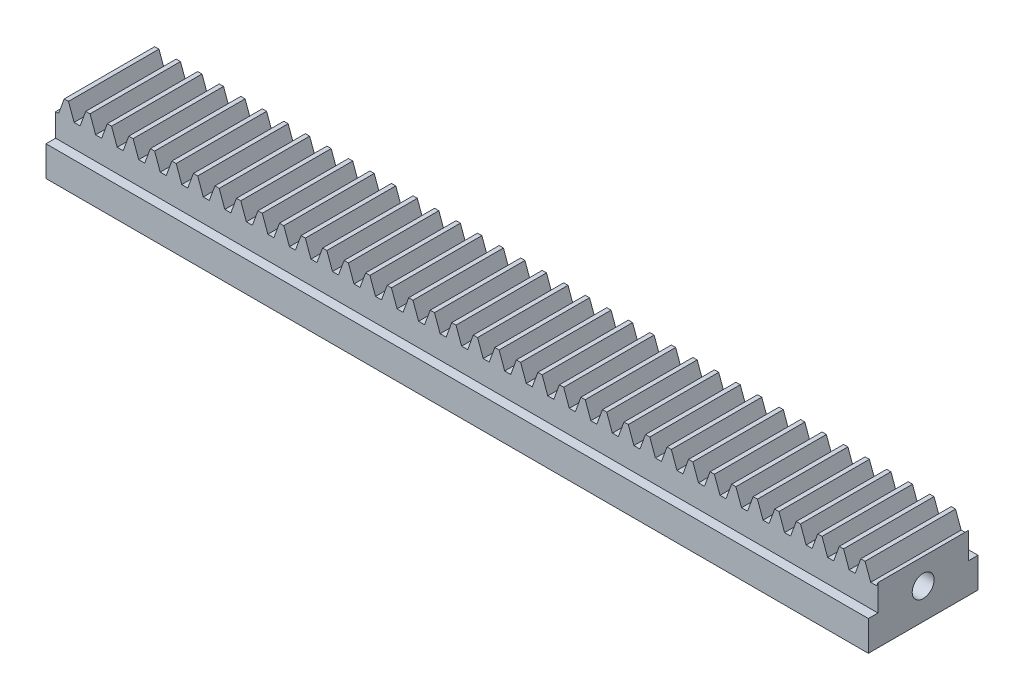
SolidWorks part; units mm, degrees
extrude "Blank" add sketch "BlankSke" against normal blind 20
sketch "BlankSke" plane through (0, 0, 0) normal (0, 0, 1) x (1, 0, 0)
  line L1 (0, 0) -> (150, 0)
  line L2 (0, 0) -> (0, 12.5)
  line L3 (0, 12.5) -> (150, 12.5)
  line L4 (150, 0) -> (150, 12.5)
  dimension "Length" = 150
  dimension "Blank_height" = 12.5
ref_plane "Plane1" through (0, 0, 0) normal (0, 0, 1) x (1, 0, 0)
ref_plane "Plane2" through (0, 0, 0) normal (0, 1, 0) x (1, 0, 0)
ref_plane "Plane3" through (0, 0, 0) normal (1, 0, 0) x (0, 0, -1)
other "Configuration Table"
sketch "HoldingSke" plane through (0, 0, 0) normal (0, 1, 0) x (1, 0, 0)
  line L0 (0, 0) -> (0.1113, 0.7922)
  line L1 (-15, 0) -> (100, 0) construction
  line L2 (0, 0) -> (-2.1039, 2.3779)
  line L3 (0, 0) -> (-11.863, 4.5341)
  line L4 (0, 0) -> (6.6156, 5.5511)
  line L5 (0, 0) -> (-23.7986, -8.8762)
  line L6 (0, 0) -> (-10.5278, -7.1032)
  line L9 (-71.009, 38.7566) -> (69.9449, 90.0596)
  line L10 (-76.2, 3.6279) -> (-64.95, 3.6279)
  line L11 (0, 0) -> (-7, 0)
  line L12 (-76.2, 101.6) -> (-76.155, 101.6)
  line L13 (24.9733, 27.94) -> (52.9518, 28.4284)
  line L14 (24.9733, 27.94) -> (24.9743, 27.94)
  line L15 (24.9733, 27.94) -> (100.4006, 29.5858)
  circle A0 centre (0, 0) radius 19.05
  circle A1 centre (0, 0) radius 5.625
  circle A2 centre (0, 0) radius 12.7
  dimension "MPH" = 11.25
  dimension "Diameter" = 38.1
  dimension "Num_teeth" = 40
  dimension "Pitch" = 0.8
  dimension "Show_teeth" = 998
  dimension "Thickness" = 12.7
  dimension "Ap" = 20
  dimension "Pitch_height" = 11.25
  dimension "Width" = 7
  dimension "Backlash" = 0.045
  dimension "Addendum_fac" = 1
  dimension "Dedendum_fac" = 1.25
  dimension "Clearance_fac" = 0.25
  dimension "Dedendum_add" = 0.001
  dimension "Length" = 150
  dimension "Module" = 1.25
sketch "TooCutSkeIll" plane through (0, 0, 0) normal (0, 0, 1) x (1, 0, 0)
  line L0 (-1.5597, 12.4671) -> (-0.6231, 9.8938)
  line L1 (-0.3285, 9.6875) -> (0.3285, 9.6875)
  line L2 (0.6231, 9.8938) -> (1.5597, 12.4671)
  line L3 (150, 12.5) -> (0, 12.5) construction
  line L4 (0, 0) -> (0, 64.897) construction
  line L5 (-13.208, 11.25) -> (12.954, 11.25) construction
  line L6 (0, 0) -> (150, 0) construction
  line L7 (1.1167, 11.25) -> (1.1167, 48.7463) construction
  line L8 (-1.1167, 11.25) -> (-1.1167, 48.7463) construction
  line L9 (1.6067, 12.5) -> (1.6067, 12.5254)
  line L10 (-1.6067, 12.5) -> (-1.6067, 12.5254)
  line L11 (-1.6067, 12.5254) -> (1.6067, 12.5254)
  arc A0 (0.3285, 9.6875) -> (0.6231, 9.8938) centre (0.3285, 10.001) ccw
  arc A1 (-0.6231, 9.8938) -> (-0.3285, 9.6875) centre (-0.3285, 10.001) ccw
  arc A2 (1.6067, 12.5) -> (1.5597, 12.4671) centre (1.6067, 12.45) ccw
  arc A3 (-1.5597, 12.4671) -> (-1.6067, 12.5) centre (-1.6067, 12.45) ccw
  dimension "Pitch_height" = 11.25
  dimension "Addendum_plus" = 1.2754
  dimension "Pressure_angle" = 20
  dimension "Gap_width" = 2.2335
  dimension "Dedendum" = 1.5625
extrude "ToothCutIll" [suppressed] cut sketch "TooCutSkeIll" against normal through all
sketch "TooCutSkeSim" plane through (0, 0, 0) normal (0, 0, 1) x (1, 0, 0)
  line L0 (0.548, 9.6875) -> (-0.548, 9.6875)
  line L1 (1.581, 12.5254) -> (0.548, 9.6875)
  line L2 (0, 17.4625) -> (0, 53.467) construction
  line L3 (1.581, 12.5254) -> (-1.581, 12.5254)
  line L6 (-1.581, 12.5254) -> (-0.548, 9.6875)
  line L9 (-1.1167, 11.25) -> (1.1167, 11.25) construction
  line L10 (0, 0) -> (150, 0) construction
  line L11 (1.1167, 11.25) -> (1.1167, 53.467) construction
  line L12 (-1.1167, 11.25) -> (-1.1167, 53.467) construction
  dimension "Pitch_height" = 11.25
  dimension "Addendum_plus" = 1.2754
  dimension "Pressure_angle" = 20
  dimension "Gap_width" = 2.2335
  dimension "Dedendum" = 1.5625
extrude "ToothCutSim" cut sketch "TooCutSkeSim" against normal through all
pattern_linear "TeethCuts" count 39 spacing 3.927 along (1, 0, 0) of "ToothCutIll", "ToothCutSim"
sketch "Croquis3" plane through (0, 0, 0) normal (0, 0, 1) x (1, 0, 0)
  line L0 (0, 9.6875) -> (0, 0) construction
  line L1 (0, 5.5) -> (150.5773, 5.5)
  line L2 (0, 5.5) -> (0, 12.8527)
  line L3 (0, 12.8527) -> (150.5773, 12.8527)
  line L4 (150.5773, 5.5) -> (150.5773, 12.8527)
  line L5 (123.408, 0) -> (123.408, 5.5) construction
  line L6 (0, 0) -> (150, 0) construction
  dimension "D1" = 5.5
extrude "Cortar-Extruir1" cut sketch "Croquis3" against normal blind 1.75
sketch "Croquis4" plane through (0, 0, -20) normal (0, 0, -1) x (-1, 0, 0)
  line L0 (-150, 0) -> (-150, 10.3093) construction
  line L1 (-150, 5.5) -> (0, 5.5)
  line L2 (-150, 5.5) -> (-150, 14.4015)
  line L3 (-150, 14.4015) -> (0, 14.4015)
  line L4 (0, 5.5) -> (0, 14.4015)
  line L5 (0, 0) -> (-150, 0) construction
  dimension "D1" = 5.5
extrude "Cortar-Extruir2" cut sketch "Croquis4" against normal blind 1.75
sketch "Croquis5" plane through (150, 0, 0) normal (1, 0, 0) x (0, 0, -1)
  line L0 (0, 0) -> (18.25, 10.3093) construction
  line L1 (18.25, 10.3093) -> (1.75, 10.3093) construction
  line L2 (1.75, 10.3093) -> (20, 0) construction
  circle A0 centre (10, 5.6489) radius 2
  dimension "D1" = 4
extrude "Cortar-Extruir3" cut sketch "Croquis5" against normal blind 10
equation "' \"Module@HoldingSke\" = 6.35"
equation "' \"Num_teeth@HoldingSke\" = 12"
equation "' \"Ap@HoldingSke\" =  20"
equation "' \"Ap@HoldingSke\" = 20"
equation "' \"Width@HoldingSke\" = 0.25 * 25.4"
equation "' \"Show_teeth@HoldingSke\" = 500"
equation "' \"Backlash@HoldingSke\" = 0.009 * 25.4"
equation "' \"Addendum_fac@HoldingSke\" = 1.0"
equation "' \"Dedendum_fac@HoldingSke\" = 1.25"
equation "' \"Dedendum_add@HoldingSke\" = 0.00005 * 25.4"
equation "' \"Clearance_fac@HoldingSke\" = 0.25"
equation "' \"Pitch_height@HoldingSke\" = 1 * 25.4"
equation "' \"Length@HoldingSke\" = 4.71 * 25.4"
equation "\"Pitch@HoldingSke\" = 1 / \"Module@HoldingSke\""
equation "\"MPH@HoldingSke\" = \"Dedendum_fac@HoldingSke\" / \"Pitch@HoldingSke\" + 2 * \"Dedendum_add@HoldingSke\" + 0.002 * 25.4"
equation "\"MPH@HoldingSke\" = ((sgn( \"MPH@HoldingSke\" - \"Pitch_height@HoldingSke\")+1)*( \"MPH@HoldingSke\" - \"Pitch_height@HoldingSke\"))/2 + \"Pitch_height@HoldingSke\""
equation "\"Blank_height@BlankSke\" = \"Pitch_height@HoldingSke\" + \"Addendum_fac@HoldingSke\"  / \"Pitch@HoldingSke\" "
equation "\"Length@BlankSke\" =  \"Length@HoldingSke\""
equation "\"Pressure_angle@TooCutSkeIll\" = \"Ap@HoldingSke\""
equation "\"Addendum_plus@TooCutSkeIll\" =  \"Addendum_fac@HoldingSke\"  / \"Pitch@HoldingSke\" + 0.001 *25.4"
equation "\"Dedendum@TooCutSkeIll\" = \"Dedendum_fac@HoldingSke\"  / \"Pitch@HoldingSke\""
equation "\"Pitch_height@TooCutSkeIll\" =  \"MPH@HoldingSke\""
equation "\"Gap_width@TooCutSkeIll\" = 3.14159265 / 2 / \"Pitch@HoldingSke\" + 6 * \"Backlash@HoldingSke\""
equation "\"Pressure_angle@TooCutSkeSim\" = \"Ap@HoldingSke\""
equation "\"Addendum_plus@TooCutSkeSim\" =  \"Addendum_fac@HoldingSke\"  / \"Pitch@HoldingSke\" + 0.001 * 25.4"
equation "\"Dedendum@TooCutSkeSim\" = \"Dedendum_fac@HoldingSke\"  / \"Pitch@HoldingSke\""
equation "\"Pitch_height@TooCutSkeSim\" =  \"MPH@HoldingSke\""
equation "\"Gap_width@TooCutSkeSim\" = 3.14159265 / 2 / \"Pitch@HoldingSke\" + 6 * \"Backlash@HoldingSke\""
equation "\"Root_fillet@TooCutSkeIll\" = \"Clearance_fac@HoldingSke\" / \"Pitch@HoldingSke\" + \"Dedendum_add@HoldingSke\""
equation "\"Break_rad@TooCutSkeIll\" = 0.02 / \"Pitch@HoldingSke\" * 2"
equation "\"Linear_pitch@TeethCuts\" = 3.14159265 / \"Pitch@HoldingSke\""
equation "\"Num_teeth@HoldingSke\" = int( ( \"Length@HoldingSke\" + 0 ) / (3.14159265 / \"Pitch@HoldingSke\")) + 0.9999  + 1"
equation " \"Num_teeth@TeethCuts\" = int( \"Show_teeth@HoldingSke\" ) + 1"
equation " \"Num_teeth@TeethCuts\" = ((sgn( \"Num_teeth@TeethCuts\" - \"Num_teeth@HoldingSke\" )-1)*( \"Num_teeth@TeethCuts\" - \"Num_teeth@HoldingSke\" ))/-2+ \"Num_teeth@HoldingSke\""
equation " \"Num_teeth@TeethCuts\" = ((sgn( \"Num_teeth@TeethCuts\" - 2.0)+1)*( \"Num_teeth@TeethCuts\" - 2.0))/2 +2.0"
